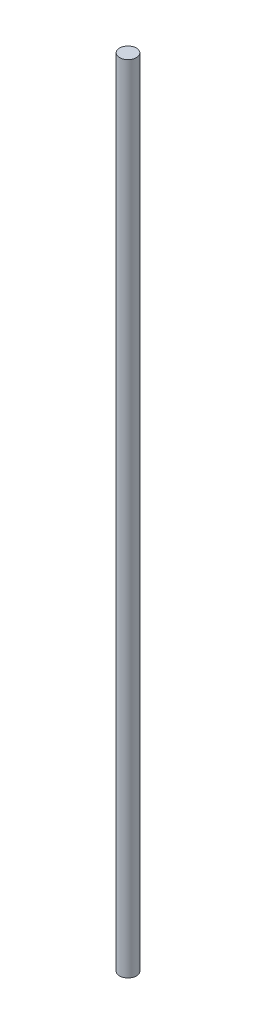
SolidWorks part; units mm, degrees
ref_plane "Front Plane" through (0, 0, 0) normal (0, 0, 1) x (1, 0, 0)
ref_plane "Top Plane" through (0, 0, 0) normal (0, 1, 0) x (1, 0, 0)
ref_plane "Right Plane" through (0, 0, 0) normal (1, 0, 0) x (0, 0, -1)
sketch "Sketch1" plane through (0, 0, 0) normal (0, 1, 0) x (1, 0, 0)
  circle A0 centre (0, 0) radius 2
extrude "Boss-Extrude1" add sketch "Sketch1" along normal blind 190
